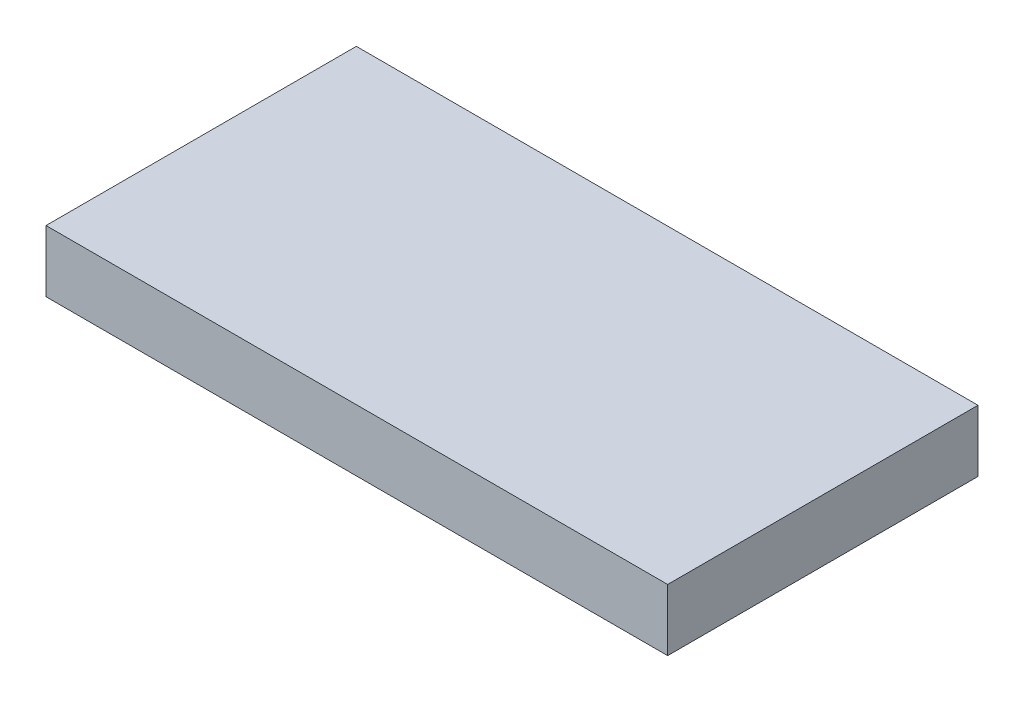
SolidWorks part; units mm, degrees
ref_plane "Front Plane" through (0, 0, 0) normal (0, 0, 1) x (1, 0, 0)
ref_plane "Top Plane" through (0, 0, 0) normal (0, 1, 0) x (1, 0, 0)
ref_plane "Right Plane" through (0, 0, 0) normal (1, 0, 0) x (0, 0, -1)
sketch "Sketch2" plane through (0, 0, 0) normal (0, 1, 0) x (1, 0, 0)
  line L1 (-15.875, 7.925) -> (15.875, 7.925)
  line L2 (-15.875, 7.925) -> (-15.875, -7.925)
  line L3 (-15.875, -7.925) -> (15.875, -7.925)
  line L4 (15.875, 7.925) -> (15.875, -7.925)
  line L5 (-15.875, 7.925) -> (15.875, -7.925) construction
  line L6 (-15.875, -7.925) -> (15.875, 7.925) construction
  point P0 (0, 0)
  dimension "D1" = 15.85
  dimension "D2" = 31.75
extrude "Boss-Extrude1" add sketch "Sketch2" against normal blind 3.15
shell "Shell1" thickness 1.5
sketch "Sketch3" plane through (0, -1.5, 0) normal (0, -1, 0) x (1, 0, 0)
  line L0 (0, 9.9148) -> (0, -9.8633) construction
  line L3 (-15.875, 7.925) -> (15.875, 7.925) construction
  circle A1 centre (0, 0) radius 2.475
  circle A2 centre (0, 0) radius 3.225
  circle A3 centre (-7.9375, 0) radius 3.225
  circle A4 centre (-7.9375, 0) radius 2.475
  circle A5 centre (7.9375, 0) radius 2.475
  circle A6 centre (7.9375, 0) radius 3.225
  dimension "D1" = 7.9375
  dimension "D2" = 6.45
  dimension "D3" = 4.95
  dimension "D4" = 2.475
  dimension "D5" = 3.225
  dimension "D6" = 7.925
extrude "Boss-Extrude2" add sketch "Sketch3" along normal offset from surface (1.45 mm away) 0.2 up to face at (0, -3.15, 0)
